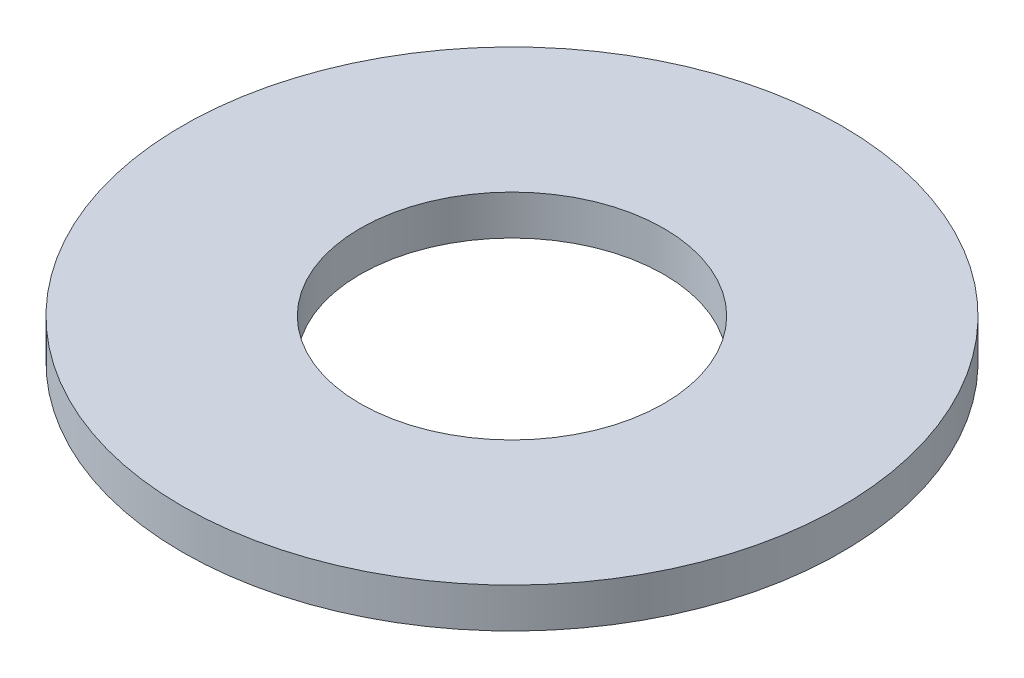
SolidWorks part; units mm, degrees
ref_plane "Front Plane" through (0, 0, 0) normal (0, 0, 1) x (1, 0, 0)
ref_plane "Top Plane" through (0, 0, 0) normal (0, 1, 0) x (1, 0, 0)
ref_plane "Right Plane" through (0, 0, 0) normal (1, 0, 0) x (0, 0, -1)
sketch "Sketch2" plane through (0, 0, 0) normal (1, 0, 0) x (0, 0, -1)
  line L0 (4.1656, 0) -> (9.0424, 0)
  line L1 (9.0424, 0) -> (9.0424, 1.0922)
  line L2 (9.0424, 1.0922) -> (4.1656, 1.0922)
  line L5 (4.1656, 1.0922) -> (4.1656, 0)
  line L6 (0, -1000) -> (0, 49000) construction
  dimension "D1" = 4.1656
  dimension "D2" = 9.0424
  dimension "D4" = 1.0922
revolve "Revolve1" add sketch "Sketch2" angle 360 about L6
